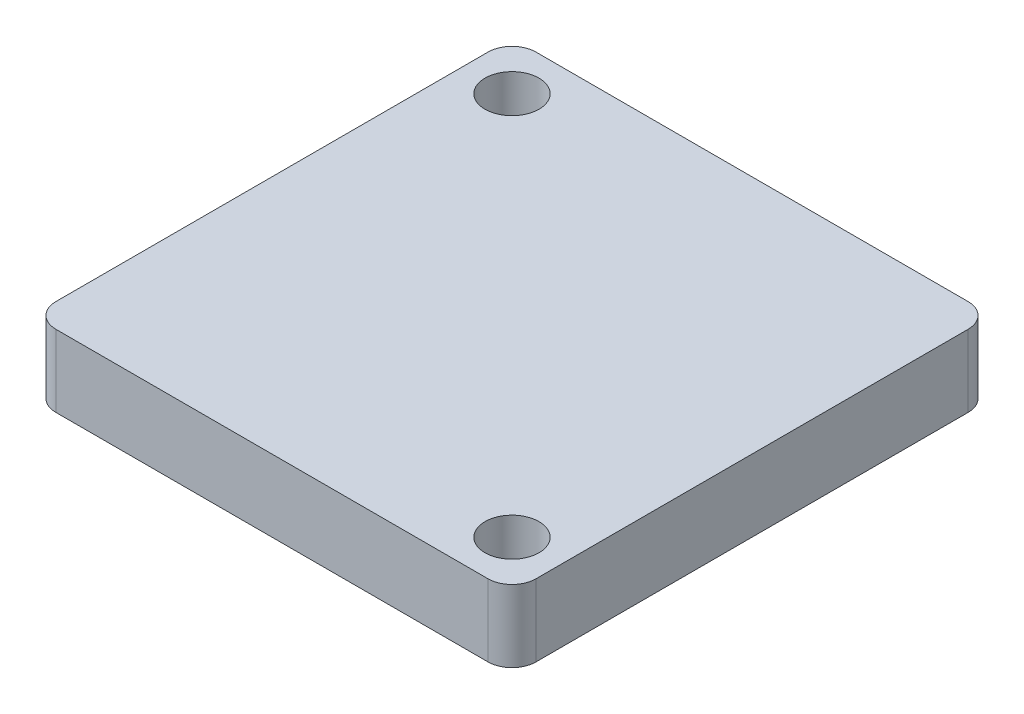
SolidWorks part; units mm, degrees
ref_plane "前视基准面" through (0, 0, 0) normal (0, 0, 1) x (1, 0, 0)
ref_plane "上视基准面" through (0, 0, 0) normal (0, 1, 0) x (1, 0, 0)
ref_plane "右视基准面" through (0, 0, 0) normal (1, 0, 0) x (0, 0, -1)
other "Configuration Table"
sketch "草图1" plane through (0, 0, 0) normal (0, 0, 1) x (1, 0, 0)
  line L0 (0, 0) -> (40, 0)
  line L1 (40, 0) -> (40, 6)
  line L2 (40, 6) -> (0, 6)
  line L3 (0, 6) -> (0, 0)
  dimension "width" = 40
  dimension "height" = 6
extrude "BlockExtrude" add sketch "草图1" along normal blind 40
fillet "Fillet" radius 2 4 edges at (0, 3, 0) (40, 3, 0) (0, 3, 40) (40, 3, 40)
sketch "草图2" plane through (0, 6, 0) normal (0, 1, 0) x (1, 0, 0)
  circle A0 centre (4, -4) radius 2.25
  dimension "diameter" = 4.5
  dimension "x" = 4
  dimension "y" = 4
extrude "Mounting_hole" cut sketch "草图2" against normal through all
sketch "草图3" plane through (0, 6, 0) normal (0, 1, 0) x (1, 0, 0)
  circle A0 centre (36, -36) radius 2.25
  dimension "diameter" = 4.5
  dimension "x" = 36
  dimension "y" = 36
extrude "切除-拉伸2" cut sketch "草图3" against normal through all
